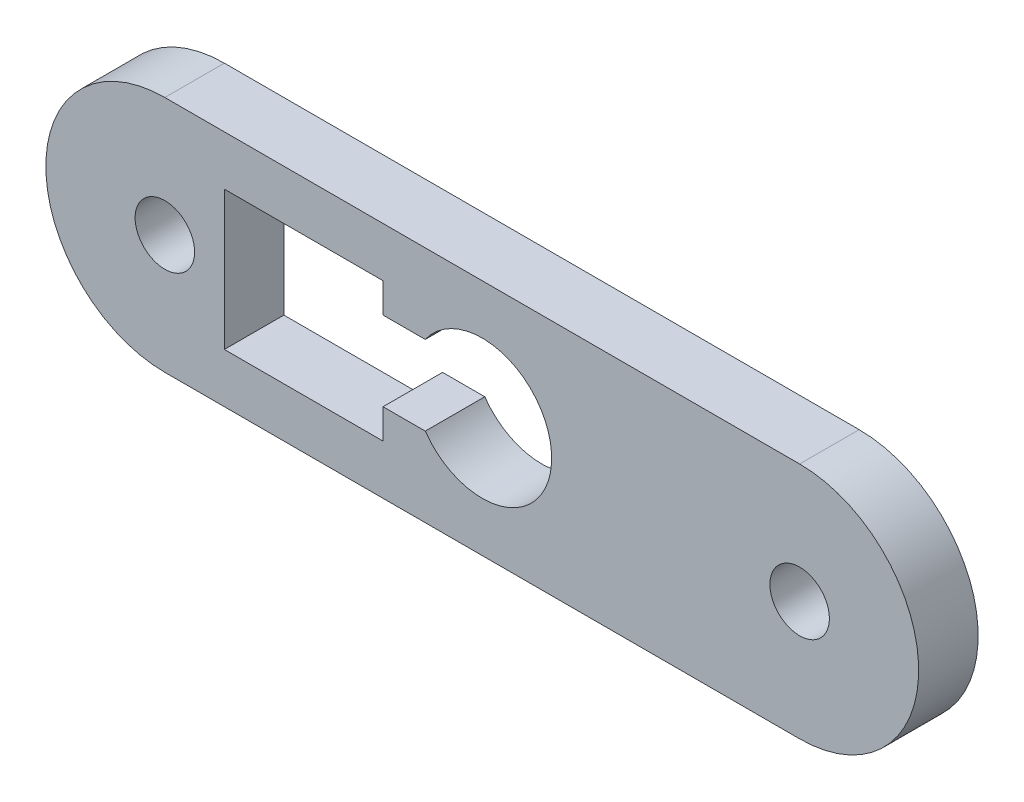
SolidWorks part; units mm, degrees
ref_plane "Front Plane" through (0, 0, 0) normal (0, 0, 1) x (1, 0, 0)
ref_plane "Top Plane" through (0, 0, 0) normal (0, 1, 0) x (1, 0, 0)
ref_plane "Right Plane" through (0, 0, 0) normal (1, 0, 0) x (0, 0, -1)
sketch "Sketch1" plane through (0, 0, 0) normal (0, 0, 1) x (1, 0, 0)
  line L0 (0, 0) -> (32, 0)
  line L1 (0, 12) -> (32, 12)
  arc A0 (32, 12) -> (32, 0) centre (32, 6) cw
  arc A1 (0, 12) -> (0, 0) centre (0, 6) ccw
  circle A2 centre (0, 6) radius 1.5
  circle A3 centre (32, 6) radius 1.5
  dimension "D1" = 32
  dimension "D3" = 3
  dimension "D2" = 12
extrude "Boss-Extrude1" add sketch "Sketch1" along normal blind 3
sketch "Sketch2" plane through (0, 0, 3) normal (0, 0, 1) x (1, 0, 0)
  line L0 (32, 12) -> (0, 12) construction
  line L1 (3, 9.5) -> (11, 9.5)
  line L2 (3, 9.5) -> (3, 2.5)
  line L3 (3, 2.5) -> (11, 2.5)
  line L4 (11, 9.5) -> (11, 8)
  line L5 (11, 8) -> (13.1277, 8)
  line L7 (11, 4) -> (13.1277, 4)
  line L9 (11, 4) -> (11, 2.5)
  arc A0 (13.1277, 4) -> (13.1277, 8) centre (16, 6) ccw
  circle A2 centre (32, 6) radius 1.5 construction
  circle A3 centre (0, 6) radius 1.5 construction
  dimension "D1" = 6
  dimension "D2" = 16
  dimension "D3" = 7
  dimension "D4" = 7
  dimension "D5" = 8
  dimension "D6" = 2.5
  dimension "D7" = 3
  dimension "D8" = 4
extrude "Cut-Extrude1" cut sketch "Sketch2" against normal through all
